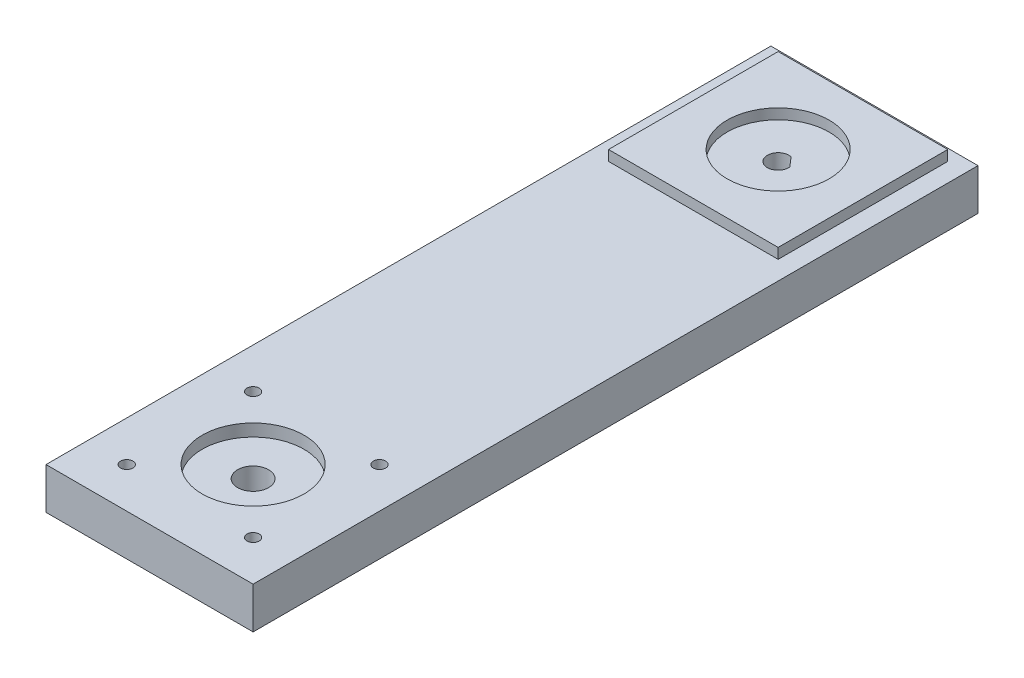
SolidWorks part; units mm, degrees
ref_plane "Front Plane" through (0, 0, 0) normal (0, 0, 1) x (1, 0, 0)
ref_plane "Top Plane" through (0, 0, 0) normal (0, 1, 0) x (1, 0, 0)
ref_plane "Right Plane" through (0, 0, 0) normal (1, 0, 0) x (0, 0, -1)
sketch "Sketch2" plane through (0, 0, 0) normal (0, 1, 0) x (-1, 0, 0)
  circle A0 centre (0, 0) radius 5.08
  dimension "D1" = 10.16
extrude "Boss-Extrude2" add sketch "Sketch2" along normal blind 41.91
sketch "Sketch3" plane through (0, 0, 0) normal (0, 0, 1) x (1, 0, 0)
  line L1 (0, 0) -> (0, 7.62) construction
  line L4 (0, 7.62) -> (0, 13.97)
  line L7 (0, 7.62) -> (-8.89, 7.62)
  line L8 (-8.89, 7.62) -> (-8.89, 13.97)
  line L9 (-8.89, 13.97) -> (0, 13.97)
  dimension "D1" = 6.35
  dimension "D2" = 8.89
  dimension "D3" = 7.62
sketch "Sketch7" plane through (0, 0, 0) normal (0, -1, 0) x (1, 0, 0)
  line L0 (0.577, -2.5995) -> (2.6291, -0.2454)
  circle A1 centre (-1.9453, 1.6968) radius 0.0101
  circle A3 centre (-0.0417, 0.0113) radius 2.6831
sketch "Sketch8" plane through (0, 41.91, 0) normal (0, 1, 0) x (1, 0, 0)
  line L1 (-25.4, 23.6223) -> (25.4, 23.6223)
  line L2 (-25.4, 23.6223) -> (-25.4, -154.1777)
  line L3 (-25.4, -154.1777) -> (25.4, -154.1777)
  line L4 (25.4, 23.6223) -> (25.4, -154.1777)
  point P4 (0, 23.6223)
  dimension "D1" = 50.8
  dimension "D2" = 177.8
extrude "Boss-Extrude3" add sketch "Sketch8" along normal blind 10.16
sketch "Sketch9" plane through (0, 41.91, 0) normal (0, -1, 0) x (1, 0, 0)
  line L0 (-25.4, 154.1777) -> (25.4, 154.1777) construction
  line L1 (0.0567, 138.8033) -> (0.1999, 138.8102)
  circle A0 centre (0, 141.4777) radius 5.08
  circle A1 centre (-1.6961, 107.3391) radius 0.0101
  circle A3 centre (0, 141.4777) radius 2.675
  dimension "D1" = 10.16
  dimension "D3" = 5.35
  dimension "D2" = 12.7
sketch "Sketch11" plane through (0, 52.07, 0) normal (0, 1, 0) x (1, 0, 0)
  line L1 (20.7996, -20.7996) -> (-20.7996, -20.7996)
  line L2 (20.7996, -20.7996) -> (20.7996, 20.7996)
  line L3 (20.7996, 20.7996) -> (-20.7996, 20.7996)
  line L4 (-20.7996, -20.7996) -> (-20.7996, 20.7996)
  line L5 (-15.5, -15.5) -> (15.5, 15.5) construction
  circle A1 centre (0, 0) radius 12.5
  circle A2 centre (-15.5, -15.5) radius 1.5 construction
  circle A3 centre (-15.5, 15.5) radius 1.5 construction
  circle A4 centre (15.5, 15.5) radius 1.5 construction
  circle A5 centre (15.5, -15.5) radius 1.5 construction
  point P5 (20.7996, 0)
  point P6 (0, 20.7996)
  point P18 (0, 0)
  point P19 (20.7996, 20.7996)
  dimension "D1" = 3
  dimension "D4" = 25
  dimension "D2" = 31
  dimension "D3" = 31
extrude "Boss-Extrude6" add sketch "Sketch11" along normal blind 2.54 contours L4 L1 L2 L3 A1
sketch "Sketch12" plane through (0, 52.07, 0) normal (0, 1, 0) x (1, 0, 0)
  line L0 (0.577, 2.5995) -> (2.6291, 0.2454)
  circle A0 centre (0, 0) radius 2.6399
extrude "Cut-Extrude1" cut sketch "Sketch12" against normal blind 25 contours L0 A0
sketch "Sketch13" plane through (0, 54.61, 0) normal (0, 1, 0) x (1, 0, 0)
  circle A0 centre (-15.5, -15.5) radius 1.5 construction
  circle A1 centre (15.5, -15.5) radius 1.5 construction
  circle A2 centre (15.5, 15.5) radius 1.5 construction
  circle A3 centre (-15.5, 15.5) radius 1.5 construction
  circle A4 centre (-15.5, -15.5) radius 1.5
  circle A5 centre (15.5, -15.5) radius 1.5
  circle A6 centre (15.5, 15.5) radius 1.5
  circle A7 centre (-15.5, 15.5) radius 1.5
sketch "Sketch14" plane through (0, 41.91, 0) normal (0, -1, 0) x (1, 0, 0)
  line L0 (25.4, 154.1777) -> (25.4, -23.6223) construction
  line L1 (-25.4, 154.1777) -> (25.4, 154.1777)
  line L2 (-25.4, 154.1777) -> (-25.4, 103.3777)
  line L3 (-25.4, 103.3777) -> (25.4, 103.3777)
  line L4 (25.4, 154.1777) -> (25.4, 103.3777)
  line L6 (-15.5, 113.2777) -> (15.5, 144.2777) construction
  circle A1 centre (0, 128.7777) radius 3.81
  circle A4 centre (15.5, 144.2777) radius 1.5
  circle A5 centre (15.5, 113.2777) radius 1.5
  circle A6 centre (-15.5, 113.2777) radius 1.5
  circle A7 centre (-15.5, 144.2777) radius 1.5
  dimension "D1" = 3
  dimension "D4" = 7.62
  dimension "D2" = 31
  dimension "D3" = 31
extrude "Cut-Extrude5" cut sketch "Sketch14" against normal blind 30.94
sketch "Sketch18" plane through (0, 52.07, 0) normal (0, 1, 0) x (1, 0, 0)
  circle A0 centre (0, -128.7777) radius 12.5
  circle A1 centre (0, -128.7777) radius 3.81 construction
  dimension "D1" = 25
extrude "Cut-Extrude6" cut sketch "Sketch18" against normal blind 3
sketch "Sketch19" plane through (-25.4, 0, 0) normal (-1, 0, 0) x (0, 0, 1)
  line L0 (-23.6223, 41.91) -> (154.1777, 41.91) construction
  line L1 (-22.415, 41.91) -> (20.1895, 41.91)
  line L2 (-22.415, 41.91) -> (-22.415, -5.0783)
  line L3 (-22.415, -5.0783) -> (20.1895, -5.0783)
  line L4 (20.1895, 41.91) -> (20.1895, -5.0783)
extrude "Cut-Extrude7" cut sketch "Sketch19" against normal blind 85.804
